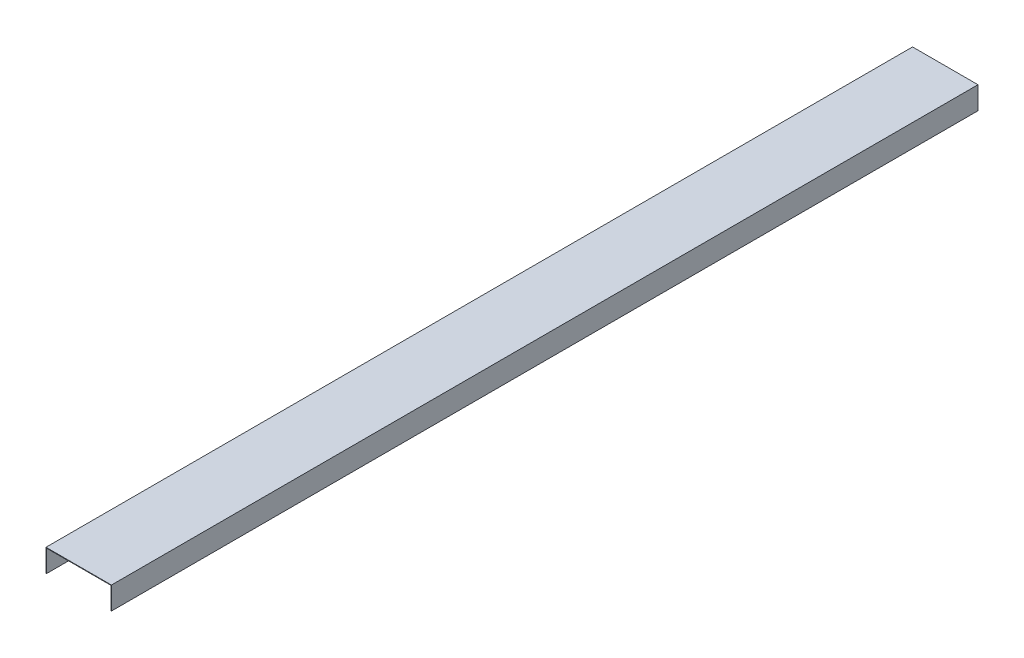
SolidWorks part; units mm, degrees
ref_plane "Front Plane" through (0, 0, 0) normal (0, 0, 1) x (1, 0, 0)
ref_plane "Top Plane" through (0, 0, 0) normal (0, 1, 0) x (1, 0, 0)
ref_plane "Right Plane" through (0, 0, 0) normal (1, 0, 0) x (0, 0, -1)
sketch "Sketch1" plane through (0, 0, 0) normal (0, 1, 0) x (1, 0, 0)
  line L1 (-46.0375, 609.6) -> (46.0375, 609.6)
  line L2 (-46.0375, 609.6) -> (-46.0375, -609.6)
  line L3 (-46.0375, -609.6) -> (46.0375, -609.6)
  line L4 (46.0375, 609.6) -> (46.0375, -609.6)
  line L5 (-46.0375, 609.6) -> (46.0375, -609.6) construction
  line L6 (-46.0375, -609.6) -> (46.0375, 609.6) construction
  point P0 (0, 0)
  dimension "D1" = 1219.2
  dimension "D2" = 92.075
extrude "Boss-Extrude1" add sketch "Sketch1" along normal blind 31.75
sketch "Sketch2" plane through (0, 0, 0) normal (0, 1, 0) x (1, 0, 0)
  line L0 (-46.0375, -609.6) -> (46.0375, -609.6) construction
  line L1 (-45.2755, 609.6) -> (45.2755, 609.6)
  line L2 (-45.2755, 609.6) -> (-45.2755, -609.6)
  line L3 (-45.2755, -609.6) -> (45.2755, -609.6)
  line L4 (45.2755, 609.6) -> (45.2755, -609.6)
  line L5 (-45.2755, 609.6) -> (45.2755, -609.6) construction
  line L6 (-45.2755, -609.6) -> (45.2755, 609.6) construction
  line L7 (46.0375, -609.6) -> (46.0375, 609.6) construction
  point P0 (0, 0)
  dimension "D1" = 0.762
extrude "Cut-Extrude1" cut sketch "Sketch2" along normal blind 30.988
